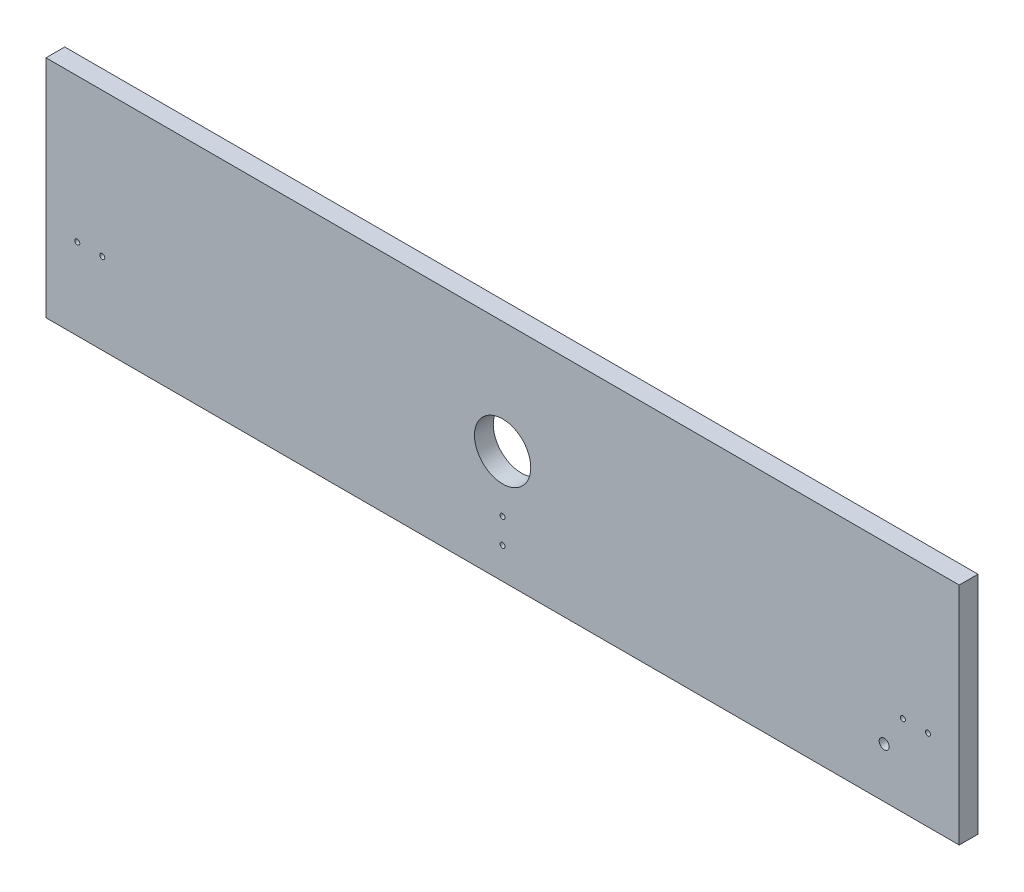
SolidWorks part; units mm, degrees
ref_plane "Alzado" through (0, 0, 0) normal (0, 0, 1) x (1, 0, 0)
ref_plane "Planta" through (0, 0, 0) normal (0, 1, 0) x (1, 0, 0)
ref_plane "Vista lateral" through (0, 0, 0) normal (1, 0, 0) x (0, 0, -1)
sketch "Croquis1" plane through (0, 0, 0) normal (0, 0, 1) x (1, 0, 0)
  line L1 (-365, -90) -> (365, -90)
  line L2 (-365, -90) -> (-365, 90)
  line L3 (-365, 90) -> (365, 90)
  line L4 (365, -90) -> (365, 90)
  line L5 (-365, -90) -> (365, 90) construction
  line L6 (-365, 90) -> (365, -90) construction
  point P0 (0, 0)
extrude "Saliente-Extruir1" add sketch "Croquis1" along normal blind 15
sketch "Croquis2" plane through (0, 0, 15) normal (0, 0, 1) x (1, 0, 0)
  line L0 (-365, -90) -> (365, -90) construction
  line L1 (-365, 90) -> (-365, -90) construction
  line L2 (365, -90) -> (365, 90) construction
  circle A0 centre (-340, -25) radius 2
  circle A1 centre (0, -65) radius 2
  circle A2 centre (0, -45) radius 2
  circle A3 centre (-320, -25) radius 2
  circle A4 centre (340, -25) radius 2
  circle A5 centre (320, -25) radius 2
  point P7 (0, -90)
  dimension "D1" = 25
  dimension "D3" = 25
  dimension "D7" = 25
  dimension "D2" = 20
  dimension "D4" = 20
  dimension "D5" = 65
  dimension "D6" = 0
  dimension "D8" = 20
  dimension "D9" = 65
extrude "Cortar-Extruir1" cut sketch "Croquis2" against normal blind 10
sketch "Croquis3" plane through (0, 0, 15) normal (0, 0, 1) x (1, 0, 0)
  circle A0 centre (0, 0) radius 22.5
extrude "Cortar-Extruir2" cut sketch "Croquis3" against normal up to surface (15 mm away) up to face at (0, 0, 0)
sketch "Croquis4" plane through (0, 0, 0) normal (0, 0, -1) x (-1, 0, 0)
  line L0 (365, -90) -> (-365, -90) construction
  line L1 (-365, -90) -> (-365, 90) construction
  circle A0 centre (-305, -50) radius 4
  dimension "D1" = 40
  dimension "D2" = 60
extrude "Cortar-Extruir3" cut sketch "Croquis4" against normal up to surface (15 mm away) up to face at (22.5, 0, 15)
